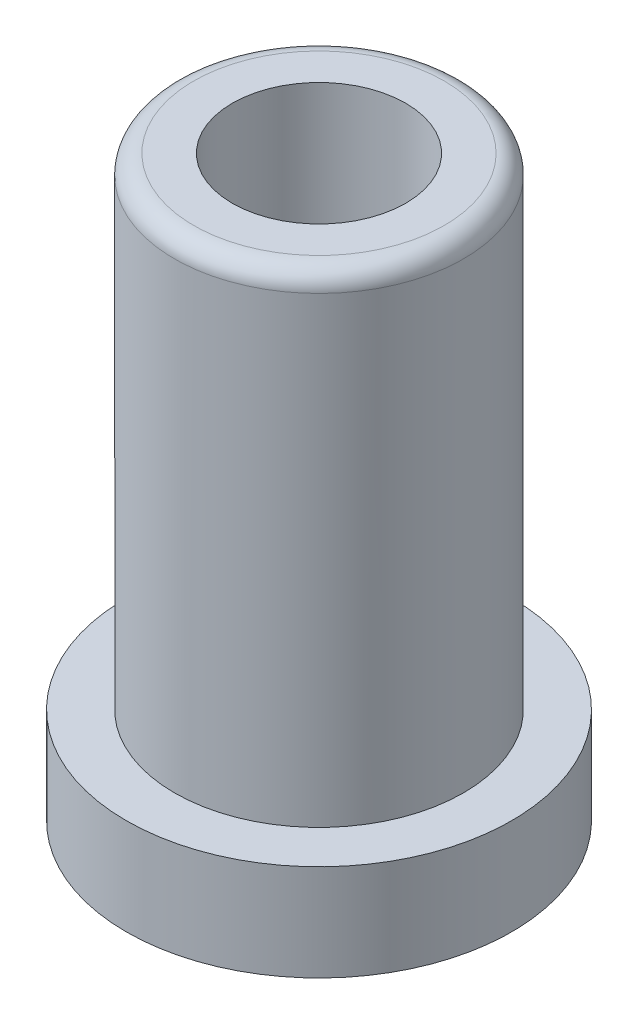
SolidWorks part; units mm, degrees
ref_plane "Ebene vorne" through (0, 0, 0) normal (0, 0, 1) x (1, 0, 0)
ref_plane "Ebene oben" through (0, 0, 0) normal (0, 1, 0) x (1, 0, 0)
ref_plane "Ebene rechts" through (0, 0, 0) normal (1, 0, 0) x (0, 0, -1)
sketch "Skizze1" plane through (0, 0, 0) normal (0, 1, 0) x (1, 0, 0)
  circle A0 centre (0, 0) radius 1
  dimension "D1" = 2
extrude "Aufsatz-Linear austragen1" add sketch "Skizze1" along normal blind 0.5
sketch "Skizze2" plane through (0, 0, 0) normal (0, -1, 0) x (1, 0, 0)
  circle A0 centre (0, 0) radius 0.75
  dimension "D1" = 1.5
extrude "Aufsatz-Linear austragen2" add sketch "Skizze2" against normal blind 3
fillet "Verrundung1" radius 0.1 1 edges at (0, 3, -0.75)
sketch "Skizze3" plane through (0, 3, 0) normal (0, 1, 0) x (1, 0, 0)
  circle A0 centre (0, 0) radius 0.45
  dimension "D1" = 0.9
extrude "Schnitt-Linear austragen1" cut sketch "Skizze3" against normal up to surface (2.5 mm away) up to face at (0, 0.5, 0.75)
